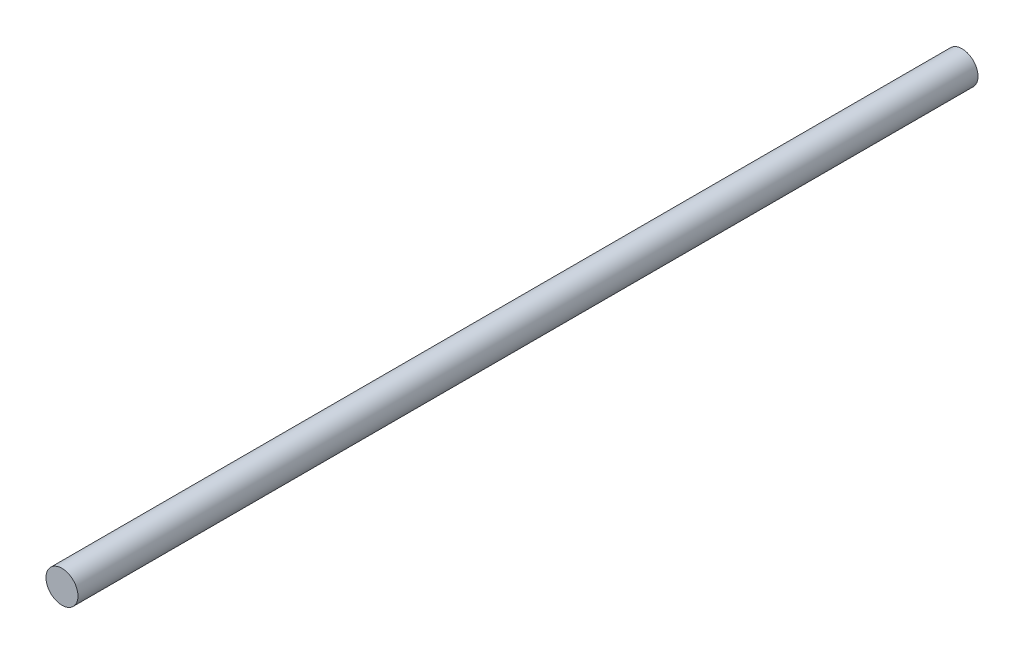
SolidWorks part; units mm, degrees
ref_plane "Front Plane" through (0, 0, 0) normal (0, 0, 1) x (1, 0, 0)
ref_plane "Top Plane" through (0, 0, 0) normal (0, 1, 0) x (1, 0, 0)
ref_plane "Right Plane" through (0, 0, 0) normal (1, 0, 0) x (0, 0, -1)
sketch "Sketch1" plane through (0, 0, 0) normal (0, 0, 1) x (1, 0, 0)
  circle A0 centre (0, 0) radius 4
  dimension "D1" = 8
extrude "Boss-Extrude1" add sketch "Sketch1" along normal mid plane 225
